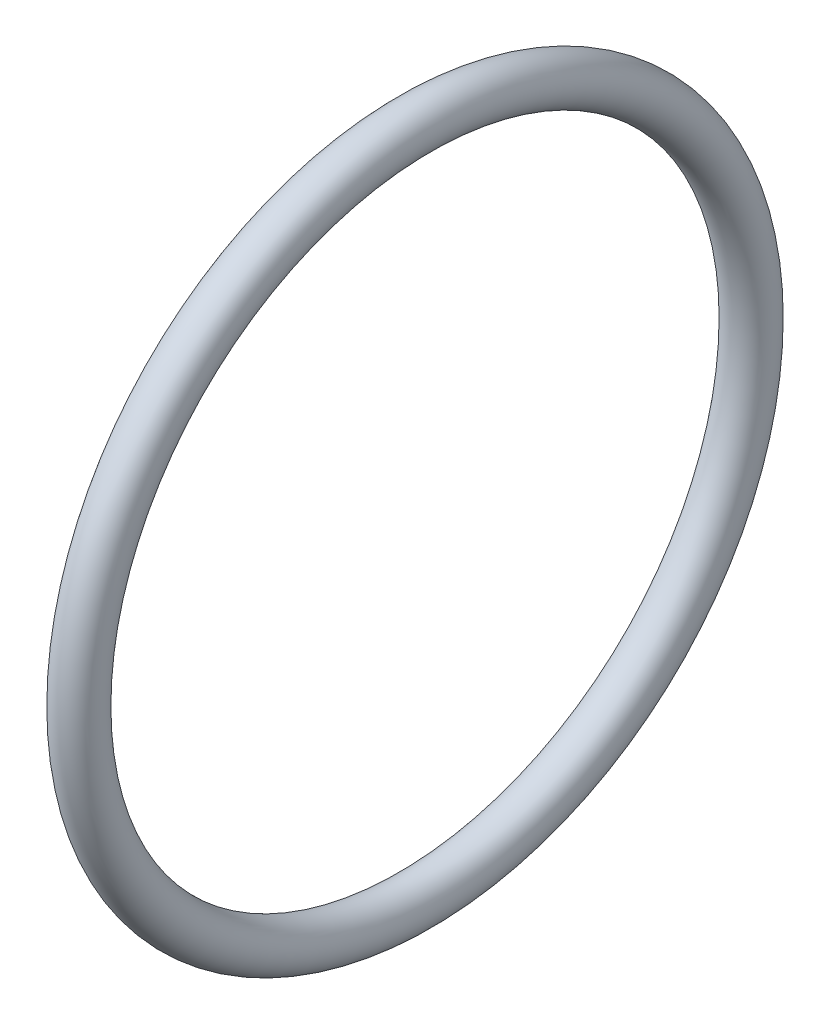
SolidWorks part; units mm, degrees
ref_plane "Front Plane" through (0, 0, 0) normal (0, 0, 1) x (1, 0, 0)
ref_plane "Top Plane" through (0, 0, 0) normal (0, 1, 0) x (1, 0, 0)
ref_plane "Right Plane" through (0, 0, 0) normal (1, 0, 0) x (0, 0, -1)
sketch "Sketch1" plane through (0, 0, 0) normal (0, 0, 1) x (1, 0, 0)
  line L0 (0, 0) -> (-1.1695, 0)
  circle A0 centre (0, 19.3929) radius 1.3081
  dimension "D1" = 2.6162
  dimension "D2" = 19.3929
revolve "Revolve1" add sketch "Sketch1" angle 360 about L0
